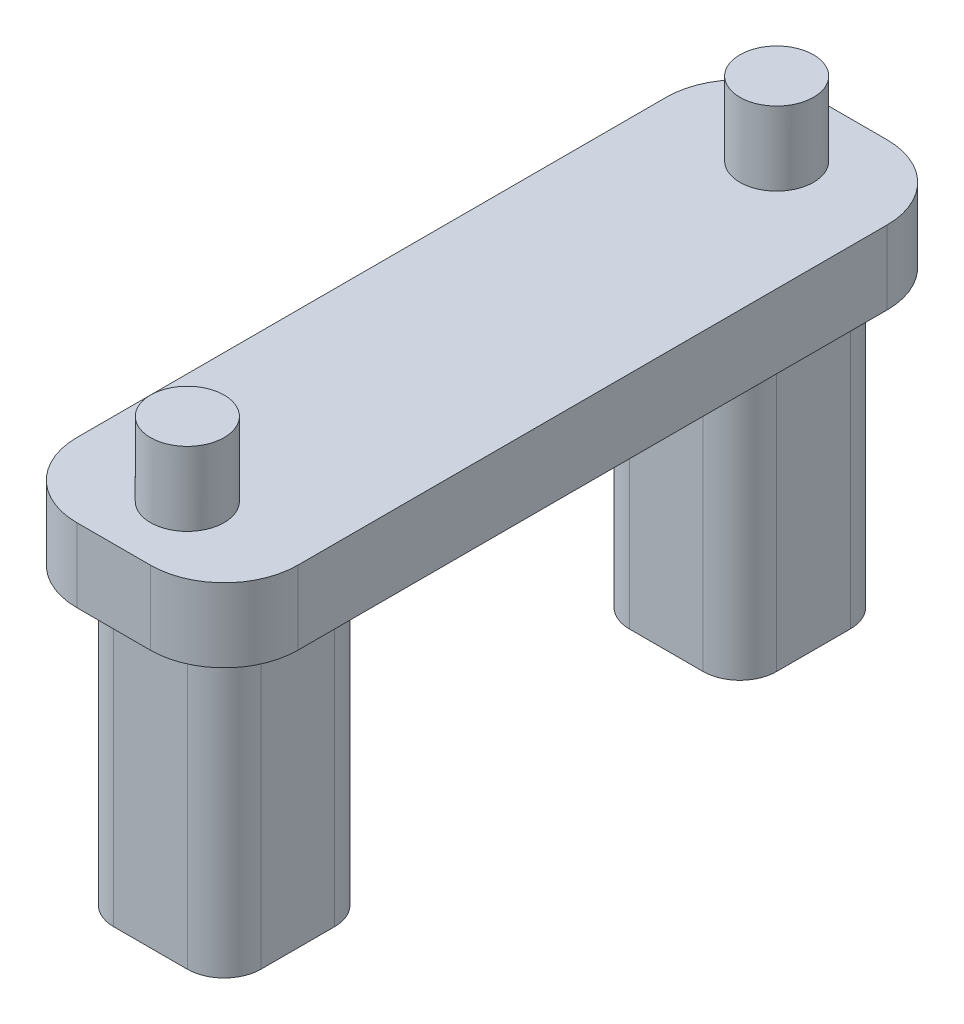
SolidWorks part; units mm, degrees
material "1060 Alloy"
ref_plane "Front Plane" through (0, 0, 0) normal (0, 0, 1) x (1, 0, 0)
ref_plane "Top Plane" through (0, 0, 0) normal (0, 1, 0) x (1, 0, 0)
ref_plane "Right Plane" through (0, 0, 0) normal (1, 0, 0) x (0, 0, -1)
sketch "Sketch1" plane through (0, 0, 0) normal (0, 1, 0) x (1, 0, 0)
  line L1 (-15, -50) -> (15, -50)
  line L2 (-15, -50) -> (-15, 50)
  line L3 (-15, 50) -> (15, 50)
  line L4 (15, -50) -> (15, 50)
  line L5 (-15, -50) -> (15, 50) construction
  line L6 (-15, 50) -> (15, -50) construction
  point P0 (0, 0)
  dimension "D1" = 30
  dimension "D2" = 100
extrude "Boss-Extrude1" add sketch "Sketch1" along normal blind 10
sketch "Sketch2" plane through (0, 10, 0) normal (0, 1, 0) x (1, 0, 0)
  line L0 (15, 50) -> (-15, 50) construction
  line L1 (0, -5.5) -> (0, 5.5) construction
  line L2 (-15, -50) -> (15, -50) construction
  circle A0 centre (0, 40) radius 5
  circle A1 centre (0, -40) radius 5
  dimension "D1" = 10
  dimension "D2" = 10
  dimension "D3" = 10
  dimension "D4" = 10
extrude "Boss-Extrude2" add sketch "Sketch2" along normal blind 10
fillet "Fillet1" radius 10 4 edges at (-15, 5, -50) (15, 5, -50) (-15, 5, 50) (15, 5, 50)
sketch "Sketch3" plane through (0, 0, 0) normal (0, -1, 0) x (1, 0, 0)
  line L0 (5, -50) -> (-5, -50) construction
  line L1 (15, 40) -> (15, -40) construction
  line L2 (-5, 50) -> (5, 50) construction
  line L3 (-15, -40) -> (-15, 40) construction
  line L4 (5, -50) -> (-5, -50) construction
  line L5 (15, 40) -> (15, 30) construction
  line L6 (-5, 50) -> (5, 50) construction
  line L7 (-15, -40) -> (-15, -30) construction
  line L8 (-5, 20) -> (5, 20) construction
  line L9 (-5, -20) -> (5, -20) construction
  line L10 (15, -30) -> (15, -40) construction
  line L11 (-15, 30) -> (-15, 40) construction
  line L12 (-10, 30) -> (-10, 40)
  line L13 (-5, 25) -> (5, 25)
  line L14 (10, 40) -> (10, 30)
  line L15 (-5, 45) -> (5, 45)
  line L16 (5, -45) -> (-5, -45)
  line L17 (-10, -40) -> (-10, -30)
  line L18 (-5, -25) -> (5, -25)
  line L19 (10, -30) -> (10, -40)
  arc A0 (-15, -40) -> (-5, -50) centre (-5, -40) ccw construction
  arc A1 (5, -50) -> (15, -40) centre (5, -40) ccw construction
  arc A2 (15, 40) -> (5, 50) centre (5, 40) ccw construction
  arc A3 (-5, 50) -> (-15, 40) centre (-5, 40) ccw construction
  arc A4 (-15, -40) -> (-5, -50) centre (-5, -40) ccw construction
  arc A5 (5, -50) -> (15, -40) centre (5, -40) ccw construction
  arc A6 (15, 40) -> (5, 50) centre (5, 40) ccw construction
  arc A7 (-5, 50) -> (-15, 40) centre (-5, 40) ccw construction
  arc A8 (-5, -20) -> (-15, -30) centre (-5, -30) ccw construction
  arc A9 (-15, 30) -> (-5, 20) centre (-5, 30) ccw construction
  arc A10 (15, 30) -> (5, 20) centre (5, 30) cw construction
  arc A11 (15, -30) -> (5, -20) centre (5, -30) ccw construction
  arc A12 (-5, 45) -> (-10, 40) centre (-5, 40) ccw
  arc A13 (-10, 30) -> (-5, 25) centre (-5, 30) ccw
  arc A14 (10, 30) -> (5, 25) centre (5, 30) cw
  arc A15 (10, 40) -> (5, 45) centre (5, 40) ccw
  arc A16 (-10, -40) -> (-5, -45) centre (-5, -40) ccw
  arc A17 (-5, -25) -> (-10, -30) centre (-5, -30) ccw
  arc A18 (10, -30) -> (5, -25) centre (5, -30) ccw
  arc A19 (5, -45) -> (10, -40) centre (5, -40) ccw
  point P20 (-15, 20)
  point P25 (15, -20)
  dimension "D3" = 10
  dimension "D4" = 10
  dimension "D5" = 10
  dimension "D6" = 10
  dimension "D1" = 30
  dimension "D2" = 30
  dimension "D7" = 5
  dimension "D8" = 5
extrude "Boss-Extrude3" add sketch "Sketch3" along normal blind 40
